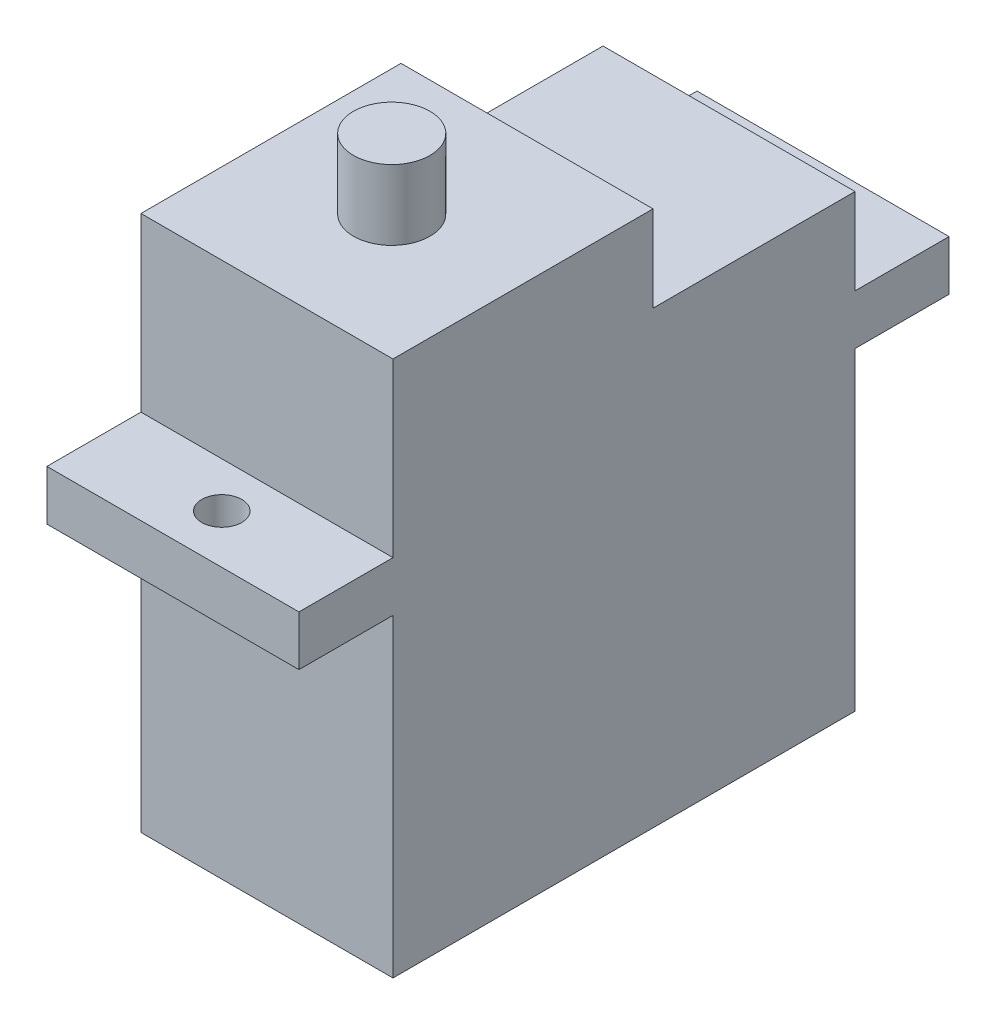
SolidWorks part; units mm, degrees
ref_plane "Front Plane" through (0, 0, 0) normal (0, 0, 1) x (1, 0, 0)
ref_plane "Top Plane" through (0, 0, 0) normal (0, 1, 0) x (1, 0, 0)
ref_plane "Right Plane" through (0, 0, 0) normal (1, 0, 0) x (0, 0, -1)
sketch "Sketch2" plane through (0, 0, 0) normal (0, 1, 0) x (1, 0, 0)
  line L1 (-6.3, 11.55) -> (6.3, 11.55)
  line L2 (-6.3, 11.55) -> (-6.3, -11.55)
  line L3 (-6.3, -11.55) -> (6.3, -11.55)
  line L4 (6.3, 11.55) -> (6.3, -11.55)
  line L5 (-6.3, 11.55) -> (6.3, -11.55) construction
  line L6 (-6.3, -11.55) -> (6.3, 11.55) construction
  point P0 (0, 0)
  dimension "D1" = 12.6
  dimension "D2" = 23.1
extrude "Boss-Extrude1" add sketch "Sketch2" along normal blind 15.7
sketch "Sketch3" plane through (0, 15.7, 0) normal (0, 1, 0) x (1, 0, 0)
  line L1 (-6.3, 16.25) -> (6.3, 16.25)
  line L2 (-6.3, 16.25) -> (-6.3, -16.25)
  line L3 (-6.3, -16.25) -> (6.3, -16.25)
  line L4 (6.3, 16.25) -> (6.3, -16.25)
  line L5 (-6.3, 16.25) -> (6.3, -16.25) construction
  line L6 (-6.3, -16.25) -> (6.3, 16.25) construction
  point P0 (0, 0)
  dimension "D1" = 12.6
  dimension "D2" = 32.5
extrude "Boss-Extrude2" add sketch "Sketch3" along normal blind 2.5
sketch "Sketch4" plane through (0, 18.2, 0) normal (0, 1, 0) x (1, 0, 0)
  line L1 (-6.3, 11.55) -> (6.3, 11.55)
  line L2 (-6.3, 11.55) -> (-6.3, -11.55)
  line L3 (-6.3, -11.55) -> (6.3, -11.55)
  line L4 (6.3, 11.55) -> (6.3, -11.55)
  line L5 (-6.3, 11.55) -> (6.3, -11.55) construction
  line L6 (-6.3, -11.55) -> (6.3, 11.55) construction
  point P0 (0, 0)
  dimension "D1" = 23.1
  dimension "D2" = 12.6
extrude "Boss-Extrude3" add sketch "Sketch4" along normal blind 4.3
sketch "Sketch5" plane through (0, 22.5, 0) normal (0, 1, 0) x (1, 0, 0)
  line L0 (-6.3, 11.55) -> (-6.3, -11.55) construction
  line L1 (6.3, -11.55) -> (-6.3, -11.55)
  line L2 (6.3, -11.55) -> (6.3, 1.45)
  line L3 (6.3, 1.45) -> (-6.3, 1.45)
  line L4 (-6.3, -11.55) -> (-6.3, 1.45)
  dimension "D1" = 13
extrude "Boss-Extrude4" add sketch "Sketch5" along normal blind 4.3 contours L3 L4 L1 L2
sketch "Sketch7" plane through (0, 26.8, 0) normal (0, 1, 0) x (1, 0, 0)
  circle A0 centre (0, -5.3129) radius 1.9129
  point P0 (0, -5.3129)
extrude "Boss-Extrude6" add sketch "Sketch7" along normal blind 3.5
sketch "Sketch8" plane through (0, 18.2, 0) normal (0, 1, 0) x (1, 0, 0)
  line L0 (-6.93, 0) -> (6.93, 0) construction
  line L1 (-6.3, 16.25) -> (0, 16.25) construction
  line L2 (-6.3, 16.25) -> (-6.3, 13.81) construction
  line L3 (-6.3, 13.81) -> (0, 13.81) construction
  line L4 (0, 16.25) -> (0, 13.81) construction
  circle A0 centre (0, 13.81) radius 1
  circle A1 centre (0, -13.81) radius 1
  dimension "D2" = 2
  dimension "D1" = 6.3
  dimension "0.245" = 2.44
extrude "Cut-Extrude1" cut sketch "Sketch8" against normal blind 3.5
ref_plane "Plane1" through (-6.3, 18.2, -16.25) normal (0, -1, 0) x (-1, 0, 0)
sketch "Sketch10" plane through (0, 30.3, 0) normal (0, 1, 0) x (1, 0, 0)
  line L0 (0, -5.3129) -> (1.9129, -5.3129)
  circle A0 centre (0, -5.3129) radius 1.9129 construction
ref_plane "Plane2" through (1.9129, 0, 0) normal (1, 0, 0) x (0, 0, -1)
sketch "Sketch12" plane through (1.9129, 0, 0) normal (1, 0, 0) x (0, 0, -1)
  line L0 (-5.3129, 30.3) -> (-5.3129, 26.8)
  line L1 (-3.4001, 30.3) -> (-7.2258, 30.3) construction
  line L2 (-11.55, 26.8) -> (1.45, 26.8) construction
  line L3 (-5.3129, 26.8) -> (-5.3129, 0)
  line L4 (-11.55, 0) -> (11.55, 0) construction
ref_plane "Plane3" through (16.3, 0, 0) normal (1, 0, 0) x (0, 0, -1)
sketch "Sketch13" plane through (16.3, 0, 0) normal (1, 0, 0) x (0, 0, -1)
  line L0 (-16.25, 16.95) -> (-5.3129, 16.95)
  line L1 (-16.25, 18.2) -> (-16.25, 15.7) construction
  line L2 (-5.3129, 26.8) -> (-5.3129, 0) construction
